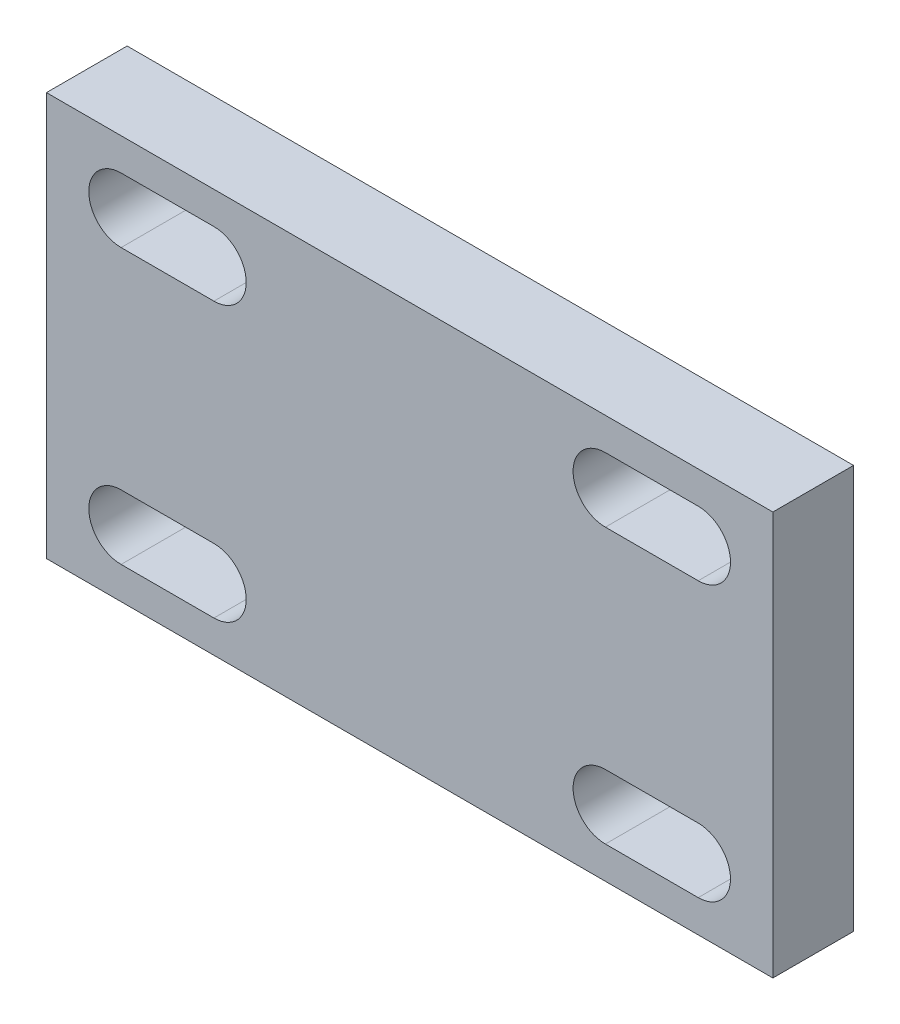
SolidWorks part; units mm, degrees
material "AISI 1045 Aço, trefilado"
ref_plane "Plano frontal" through (0, 0, 0) normal (0, 0, 1) x (1, 0, 0)
ref_plane "Plano superior" through (0, 0, 0) normal (0, 1, 0) x (1, 0, 0)
ref_plane "Plano direito" through (0, 0, 0) normal (1, 0, 0) x (0, 0, -1)
sketch "Esboço3" plane through (0, 0, 0) normal (0, 0, 1) x (1, 0, 0)
  line L0 (9.25, 42) -> (20.75, 42) construction
  line L1 (0, 0) -> (90, 0)
  line L2 (0, 0) -> (0, 50)
  line L3 (0, 50) -> (90, 50)
  line L4 (90, 0) -> (90, 50)
  line L5 (9.25, 46) -> (20.75, 46)
  line L6 (9.25, 38) -> (20.75, 38)
  line L7 (80.75, 42) -> (69.25, 42) construction
  line L8 (80.75, 38) -> (69.25, 38)
  line L9 (80.75, 46) -> (69.25, 46)
  line L10 (9.25, 8) -> (20.75, 8) construction
  line L13 (9.25, 12) -> (20.75, 12)
  line L14 (9.25, 4) -> (20.75, 4)
  line L15 (69.25, 8) -> (80.75, 8) construction
  line L16 (69.25, 12) -> (80.75, 12)
  line L17 (69.25, 4) -> (80.75, 4)
  arc A0 (9.25, 46) -> (9.25, 38) centre (9.25, 42) ccw
  arc A1 (20.75, 38) -> (20.75, 46) centre (20.75, 42) ccw
  arc A2 (80.75, 38) -> (80.75, 46) centre (80.75, 42) ccw
  arc A3 (69.25, 46) -> (69.25, 38) centre (69.25, 42) ccw
  arc A6 (9.25, 12) -> (9.25, 4) centre (9.25, 8) ccw
  arc A7 (20.75, 4) -> (20.75, 12) centre (20.75, 8) ccw
  arc A8 (69.25, 12) -> (69.25, 4) centre (69.25, 8) ccw
  arc A9 (80.75, 4) -> (80.75, 12) centre (80.75, 8) ccw
  point P7 (15, 42)
  point P12 (75, 42)
  point P21 (15, 8)
  point P28 (75, 8)
  dimension "D3" = 15
  dimension "D5" = 11.5
  dimension "D7" = 15
  dimension "D10" = 8
  dimension "D1" = 50
  dimension "D2" = 90
  dimension "D4" = 11.5
  dimension "D6" = 11.5
  dimension "D8" = 11.5
  dimension "D9" = 8
  dimension "D11" = 8
  dimension "D12" = 8
  dimension "D13" = 8
  dimension "D14" = 8
  dimension "D15" = 15
  dimension "D16" = 15
extrude "Ressalto-extrusão1" add sketch "Esboço3" along normal blind 10
